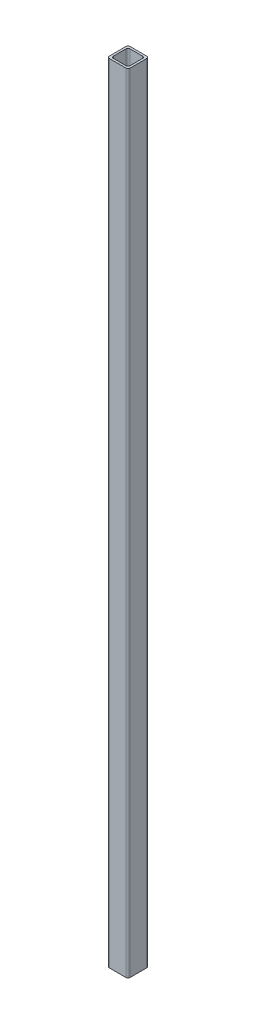
SolidWorks part; units mm, degrees
ref_plane "Front Plane" through (0, 0, 0) normal (0, 0, 1) x (1, 0, 0)
ref_plane "Top Plane" through (0, 0, 0) normal (0, 1, 0) x (1, 0, 0)
ref_plane "Right Plane" through (0, 0, 0) normal (1, 0, 0) x (0, 0, -1)
sketch "Sketch1" plane through (0, 0, 0) normal (0, 1, 0) x (1, 0, 0)
  line L1 (-51.887, -1.5435) -> (-43.887, -1.5435)
  line L2 (-52.887, -2.5435) -> (-52.887, -10.5435)
  line L3 (-51.887, -11.5435) -> (-43.887, -11.5435)
  line L4 (-42.887, -2.5435) -> (-42.887, -10.5435)
  line L5 (-50.887, -2.5435) -> (-44.887, -2.5435)
  line L6 (-51.887, -3.5435) -> (-51.887, -9.5435)
  line L7 (-50.887, -10.5435) -> (-44.887, -10.5435)
  line L8 (-43.887, -3.5435) -> (-43.887, -9.5435)
  arc A0 (-52.887, -10.5435) -> (-51.887, -11.5435) centre (-51.887, -10.5435) ccw
  arc A1 (-43.887, -11.5435) -> (-42.887, -10.5435) centre (-43.887, -10.5435) ccw
  arc A2 (-43.887, -1.5435) -> (-42.887, -2.5435) centre (-43.887, -2.5435) cw
  arc A3 (-51.887, -1.5435) -> (-52.887, -2.5435) centre (-51.887, -2.5435) ccw
  arc A4 (-50.887, -10.5435) -> (-51.887, -9.5435) centre (-50.887, -9.5435) cw
  arc A5 (-44.887, -10.5435) -> (-43.887, -9.5435) centre (-44.887, -9.5435) ccw
  arc A6 (-43.887, -3.5435) -> (-44.887, -2.5435) centre (-44.887, -3.5435) ccw
  arc A7 (-51.887, -3.5435) -> (-50.887, -2.5435) centre (-50.887, -3.5435) cw
  dimension "D1" = 1
  dimension "D8" = 1
  dimension "D2" = 10
  dimension "D3" = 10
  dimension "D4" = 1
  dimension "D5" = 1
  dimension "D6" = 1
  dimension "D7" = 1
extrude "Boss-Extrude1" add sketch "Sketch1" against normal up to surface (379.3198 mm away) from surface at -2175.9187
